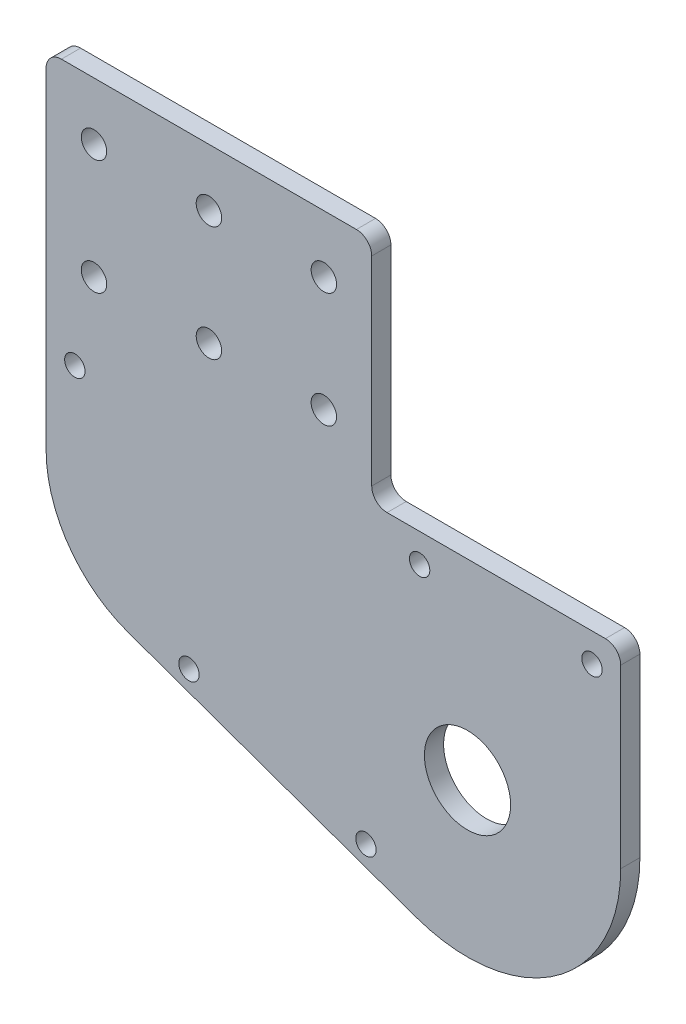
SolidWorks part; units mm, degrees
ref_plane "Front Plane" through (0, 0, 0) normal (0, 0, 1) x (1, 0, 0)
ref_plane "Top Plane" through (0, 0, 0) normal (0, 1, 0) x (1, 0, 0)
ref_plane "Right Plane" through (0, 0, 0) normal (1, 0, 0) x (0, 0, -1)
sketch "Gear&Motor Layout" plane through (0, 0, 0) normal (0, 0, 1) x (1, 0, 0)
  line L1 (-139.7, 63.5) -> (50.8, 63.5) construction
  line L2 (-98.4907, 24.9428) -> (0, 0) construction
  circle A1 centre (-98.4907, 24.9428) radius 32.2072 construction
  circle A2 centre (0, 0) radius 14.2875 construction
  circle A3 centre (-98.4907, 24.9428) radius 25.4 construction
  circle A4 centre (-123.8907, 24.9428) radius 2.5527 construction
  circle A5 centre (-98.4907, 50.3428) radius 2.5527 construction
  circle A6 centre (-73.0907, 24.9428) radius 2.5527 construction
  circle A7 centre (-98.4907, -0.4572) radius 2.5527 construction
  circle A11 centre (-50.4765, 12.7832) radius 41.91 construction
  circle A12 centre (-50.4765, 12.7832) radius 43.18 construction
  circle A15 centre (0, 0) radius 38.1 construction
  circle A16 centre (0, 0) radius 39.37 construction
  circle A17 centre (-50.4765, 12.7832) radius 13.97 construction
  circle A18 centre (-50.4765, 12.7832) radius 15.24 construction
  circle A19 centre (-98.4907, 24.9428) radius 7.62 construction
  circle A20 centre (-98.4907, 24.9428) radius 8.89 construction
  point P5 (-123.8907, 24.9428)
  point P8 (-98.4907, 50.3428)
  point P10 (-73.0907, 24.9428)
  point P14 (-98.4907, -0.4572)
  dimension "D4" = 83.82
  dimension "D1" = 28.575
  dimension "D2" = 64.4144
  dimension "D3" = 50.8
  dimension "D5" = 15.24
  dimension "D6" = 17.78
  dimension "D7" = 86.36
  dimension "D8" = 27.94
  dimension "D9" = 30.48
  dimension "D10" = 76.2
  dimension "D11" = 78.74
  dimension "D13" = 63.5
  dimension "D14" = 5.1054
  dimension "D16" = 6.35
  dimension "D12" = 50.8
  dimension "D15" = 190.5
sketch "Sketch2" plane through (0, 0, 0) normal (0, 0, 1) x (1, 0, 0)
  line L0 (50.8, 63.5) -> (-139.7, 63.5)
  line L1 (50.8, 63.5) -> (50.8, 0)
  line L2 (-17.0643, -47.8482) -> (-112.3334, -13.872)
  line L3 (-139.7, 24.9428) -> (-139.7, 63.5)
  arc A0 (50.8, 0) -> (-17.0643, -47.8482) centre (0, 0) cw
  arc A1 (-112.3334, -13.872) -> (-139.7, 24.9428) centre (-98.4907, 24.9428) cw
extrude "Boss-Extrude1" add sketch "Sketch2" against normal blind 6.35
sketch "Sketch3" plane through (0, 0, 0) normal (0, 0, 1) x (1, 0, 0)
  line L0 (-139.7, 63.5) -> (-139.7, 139.7)
  line L1 (-139.7, 139.7) -> (-31.75, 139.7)
  line L2 (-31.75, 139.7) -> (-31.75, 63.5)
  line L5 (50.8, 0) -> (50.8, 63.5) construction
  line L6 (50.8, 63.5) -> (-139.7, 63.5) construction
  line L7 (-31.75, 63.5) -> (-139.7, 63.5)
  dimension "D1" = 82.55
  dimension "D2" = 76.2
extrude "Boss-Extrude2" add sketch "Sketch3" against normal up to surface (6.35 mm away) up to face at (-50.1578, 11.3816, -6.35)
fillet "Fillet1" radius 5.08 4 edges at (50.8, 63.5, -3.175) (-31.75, 63.5, -3.175) (-31.75, 139.7, -3.175) (-139.7, 139.7, -3.175)
sketch "Sketch4" plane through (0, 0, 0) normal (0, 0, 1) x (1, 0, 0)
  circle A0 centre (0, 0) radius 14.2875 construction
  circle A1 centre (0, 0) radius 14.2875
  circle A2 centre (-50.4765, 12.7832) radius 14.2875 construction
  circle A3 centre (-98.4907, 24.9428) radius 14.2875 construction
  dimension "D1" = 28.575
extrude "Cut-Extrude1" cut sketch "Sketch4" against normal up to next
hole_wizard "1/4 Clearance Hole1" positions "Sketch11" profile "Sketch9" hole size "1/4" standard "ANSI Inch" end condition through all
sketch "Sketch11" plane through (0, 0, 0) normal (0, 0, 1) x (1, 0, 0)
  line L0 (50.8, 0) -> (50.8, 58.42) construction
  line L1 (-139.7, 63.5) -> (50.8, 63.5) construction
  line L2 (-92.345, -14.2588) -> (-33.672, -35.1836) construction
  line L4 (-112.3334, -13.872) -> (-17.0643, -47.8482) construction
  line L5 (-33.672, -35.1836) -> (-30.1524, -25.3146) construction
  line L6 (-89.3815, -5.9494) -> (-92.345, -14.2588) construction
  line L7 (-139.7, 134.62) -> (-139.7, 24.9428) construction
  circle A0 centre (-50.4765, 12.7832) radius 43.18 construction
  circle A1 centre (0, 0) radius 39.37 construction
  circle A2 centre (-98.4907, 24.9428) radius 32.2072 construction
  point P0 (-33.672, -35.1836)
  point P2 (-92.345, -14.2588)
  point P4 (-130.175, 53.975)
  point P6 (-15.875, 53.975)
  point P8 (41.275, 53.975)
  dimension "D1" = 9.525
  dimension "D2" = 9.525
  dimension "D3" = 6.35
  dimension "2" = 57.15
  dimension "D4" = 9.525
  dimension "D5" = 9.525
sketch "Sketch9" plane through (-33.672, -35.1836, 0) normal (1, 0, 0) x (0, -1, 0)
  line L0 (0, 0) -> (0, 6.35)
  line L1 (0, 6.35) -> (3.3782, 6.35)
  line L2 (3.3782, 6.35) -> (3.3782, 0)
  line L5 (3.3782, 0) -> (0, 0)
  line L11 (0, -6.35) -> (0, 107.95) construction
  dimension "Thru Hole Dia." = 6.7564
  dimension "Thru Hole Depth" = 6.35
sketch "Sketch12" plane through (0, 0, 0) normal (0, 0, 1) x (1, 0, 0)
  circle A0 centre (-47.625, 120.65) radius 4.2164 construction
  circle A1 centre (-47.625, 120.65) radius 4.2164
  circle A2 centre (-123.825, 120.65) radius 4.2164 construction
  circle A3 centre (-123.825, 82.55) radius 4.2164 construction
  circle A4 centre (-85.725, 82.55) radius 4.2164 construction
  circle A5 centre (-85.725, 120.65) radius 4.2164 construction
  circle A18 centre (-47.625, 82.55) radius 4.2164 construction
  circle A19 centre (-123.825, 120.65) radius 4.2164
  circle A20 centre (-123.825, 82.55) radius 4.2164
  circle A21 centre (-85.725, 82.55) radius 4.2164
  circle A22 centre (-85.725, 120.65) radius 4.2164
  circle A23 centre (-47.625, 120.65) radius 4.2164
  circle A24 centre (-47.625, 82.55) radius 4.2164
extrude "Cut-Extrude2" cut sketch "Sketch12" against normal up to surface (6.35 mm away) contours A19 | A20 | A22 | A21 | A24 | A1 up to face at (-30.2938, -35.1836, -6.35)
